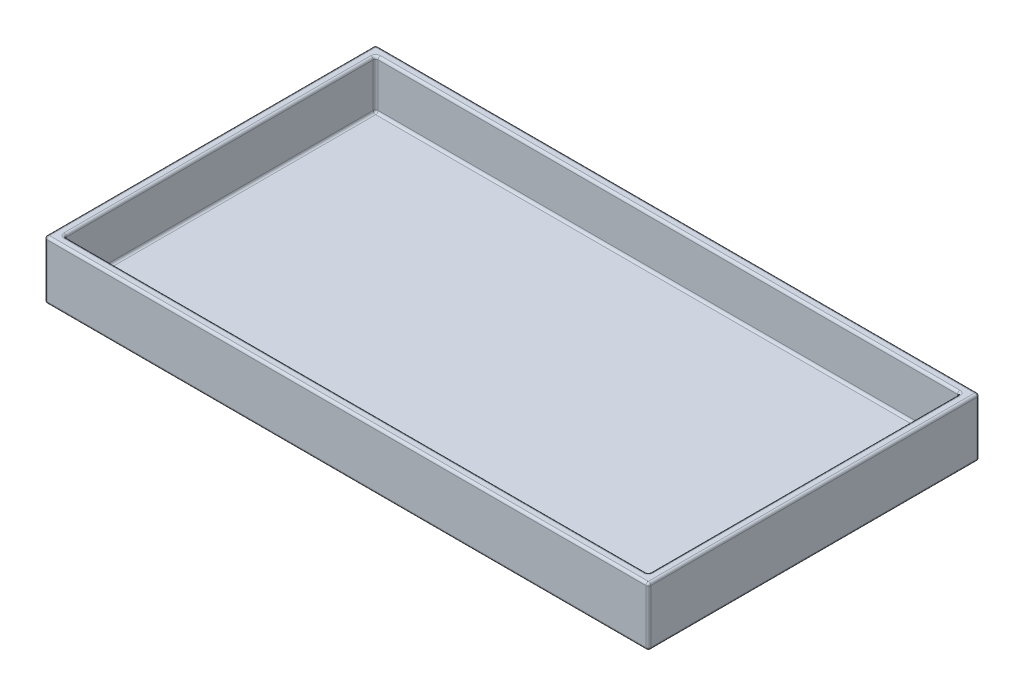
SolidWorks part; units mm, degrees
ref_plane "Front Plane" through (0, 0, 0) normal (0, 0, 1) x (1, 0, 0)
ref_plane "Top Plane" through (0, 0, 0) normal (0, 1, 0) x (1, 0, 0)
ref_plane "Right Plane" through (0, 0, 0) normal (1, 0, 0) x (0, 0, -1)
sketch "Sketch1" plane through (0, 0, 0) normal (0, 1, 0) x (1, 0, 0)
  line L1 (0, 0) -> (124, 0)
  line L2 (0, 0) -> (0, 68)
  line L3 (0, 68) -> (124, 68)
  line L4 (124, 0) -> (124, 68)
  dimension "D1" = 68
  dimension "D2" = 124
extrude "Boss-Extrude1" add sketch "Sketch1" along normal blind 12
sketch "Sketch2" plane through (0, 12, 0) normal (0, 1, 0) x (1, 0, 0)
  line L8 (2, 66) -> (2, 2)
  line L9 (2, 2) -> (122, 2)
  line L10 (122, 2) -> (122, 66)
  line L11 (122, 66) -> (2, 66)
  line L12 (2, 66) -> (2, 2)
  line L13 (2, 2) -> (122, 2)
  line L14 (122, 2) -> (122, 66)
  line L15 (122, 66) -> (2, 66)
  dimension "D2" = 64
  dimension "D3" = 120
  dimension "D1" = 2
extrude "Cut-Extrude1" cut sketch "Sketch2" against normal blind 10
fillet "Fillet1" radius 0.5 24 edges at (62, 12, -66) (2, 12, -34) (62, 12, -2) (122, 12, -34) (62, 2, -66) (2, 2, -34) (62, 2, -2) (122, 2, -34) (2, 7, -66) (2, 7, -2) (122, 7, -2) (122, 7, -66) (0, 0, -34) (62, 0, 0) (62, 0, -68) (0, 12, -34) (62, 12, 0) (124, 12, -34) (62, 12, -68) (0, 6, -68) (124, 6, -68) (124, 6, 0) (0, 6, 0) (124, 0, -34)
